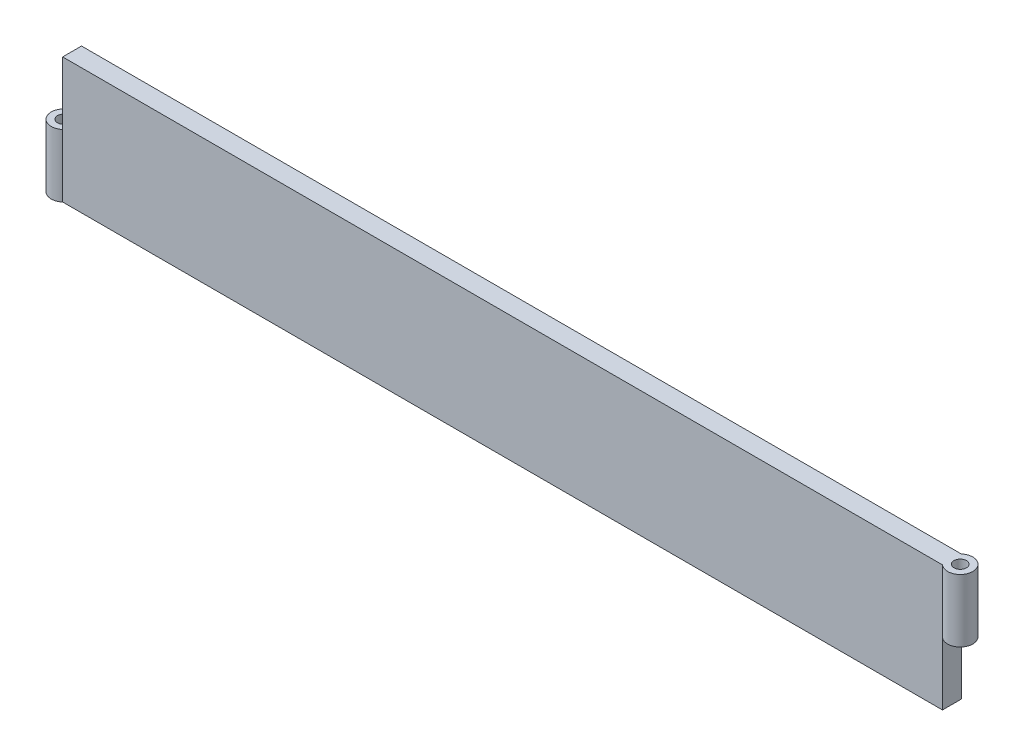
SolidWorks part; units mm, degrees
ref_plane "Front Plane" through (0, 0, 0) normal (0, 0, 1) x (1, 0, 0)
ref_plane "Top Plane" through (0, 0, 0) normal (0, 1, 0) x (1, 0, 0)
ref_plane "Right Plane" through (0, 0, 0) normal (1, 0, 0) x (0, 0, -1)
sketch "Sketch1" plane through (0, 0, 0) normal (0, 0, 1) x (1, 0, 0)
  line L1 (-25284.5528, 8821.1382) -> (-25144.5528, 8821.1382)
  line L2 (-25284.5528, 8821.1382) -> (-25284.5528, 8801.1382)
  line L3 (-25284.5528, 8801.1382) -> (-25144.5528, 8801.1382)
  line L4 (-25144.5528, 8821.1382) -> (-25144.5528, 8801.1382)
  line L5 (-25284.5528, 8821.1382) -> (-25144.5528, 8801.1382) construction
  line L6 (-25284.5528, 8801.1382) -> (-25144.5528, 8821.1382) construction
  point P0 (-25214.5528, 8811.1382)
  dimension "D1" = 20
  dimension "D2" = 140
extrude "Boss-Extrude1" add sketch "Sketch1" along normal blind 3
sketch "Sketch2" plane through (0, 8821.1382, 0) normal (0, 1, 0) x (1, 0, 0)
  line L0 (-25214.5528, -11.2225) -> (-25214.5528, 9.76) construction
  circle A2 centre (-25143.23, -1.5) radius 1
  circle A3 centre (-25143.23, -1.5) radius 2
extrude "Boss-Extrude2" add sketch "Sketch2" against normal blind 10
sketch "Sketch3" plane through (0, 8801.1382, 0) normal (0, -1, 0) x (1, 0, 0)
  circle A0 centre (-25285.8757, 1.5) radius 2
  circle A1 centre (-25285.8757, 1.5) radius 1
  dimension "D1" = 4
  dimension "D2" = 2
extrude "Boss-Extrude3" add sketch "Sketch3" against normal blind 10
